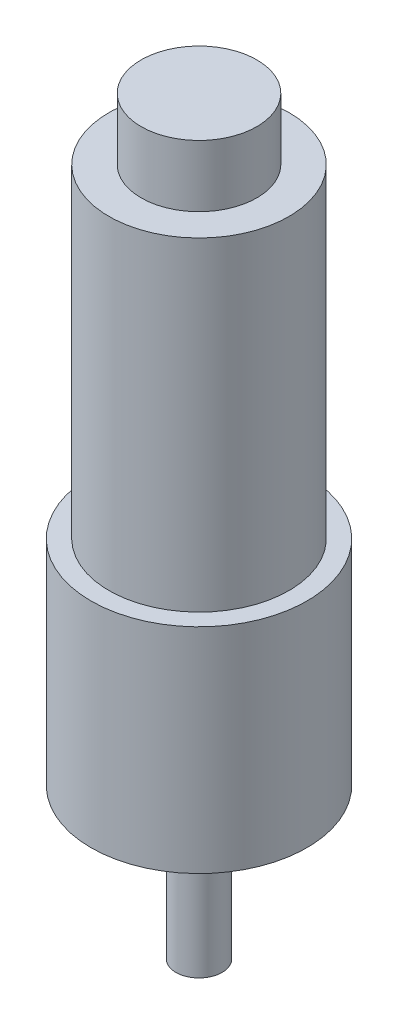
SolidWorks part; units mm, degrees
ref_plane "前视基准面" through (0, 0, 0) normal (0, 0, 1) x (1, 0, 0)
ref_plane "上视基准面" through (0, 0, 0) normal (0, 1, 0) x (1, 0, 0)
ref_plane "右视基准面" through (0, 0, 0) normal (1, 0, 0) x (0, 0, -1)
sketch "草图1" plane through (0, 0, 0) normal (0, 1, 0) x (1, 0, 0)
  circle A0 centre (0, 0) radius 14
  dimension "D1" = 28
extrude "凸台-拉伸1" add sketch "草图1" along normal blind 27.7
sketch "草图3" plane through (0, 27.7, 0) normal (0, 1, 0) x (1, 0, 0)
  circle A1 centre (0, 0) radius 11.6696
extrude "凸台-拉伸2" add sketch "草图3" along normal blind 42
sketch "草图8" plane through (0, 69.7, 0) normal (0, 1, 0) x (1, 0, 0)
  circle A0 centre (0, 0) radius 7.5
  dimension "D1" = 15
extrude "凸台-拉伸4" add sketch "草图8" along normal blind 8
sketch "草图9" plane through (0, 0, 0) normal (0, -1, 0) x (1, 0, 0)
  circle A0 centre (0, 0) radius 8
  dimension "D1" = 16
extrude "凸台-拉伸5" add sketch "草图9" along normal blind 1
sketch "草图5" plane through (0, -1, 0) normal (0, -1, 0) x (1, 0, 0)
  circle A0 centre (0, 0) radius 3
  dimension "D1" = 6
extrude "凸台-拉伸3" add sketch "草图5" along normal blind 18.5
sketch "草图7" plane through (0, -19.5, 0) normal (0, -1, 0) x (1, 0, 0)
  line L0 (-1.6583, -2.5) -> (1.6583, -2.5)
  circle A0 centre (0, 0) radius 3 construction
  arc A1 (-1.6583, -2.5) -> (1.6583, -2.5) centre (0, 0) ccw
  point P5 (0, 3)
  dimension "D1" = 5.5
extrude "切除-拉伸2" cut sketch "草图7" against normal blind 12
sketch "草图4" plane through (0, 0, 0) normal (0, -1, 0) x (1, 0, 0)
  line L0 (0, 0) -> (0, 13.5149) construction
  circle A0 centre (0, 11) radius 1.5
  circle A1 centre (0, 0) radius 11 construction
  circle A2 centre (11, 0) radius 1.5
  circle A3 centre (0, -11) radius 1.5
  circle A4 centre (-11, 0) radius 1.5
  dimension "D1" = 22
  dimension "D2" = 4
  dimension "D3" = 3
extrude "切除-拉伸1" cut sketch "草图4" against normal blind 4
